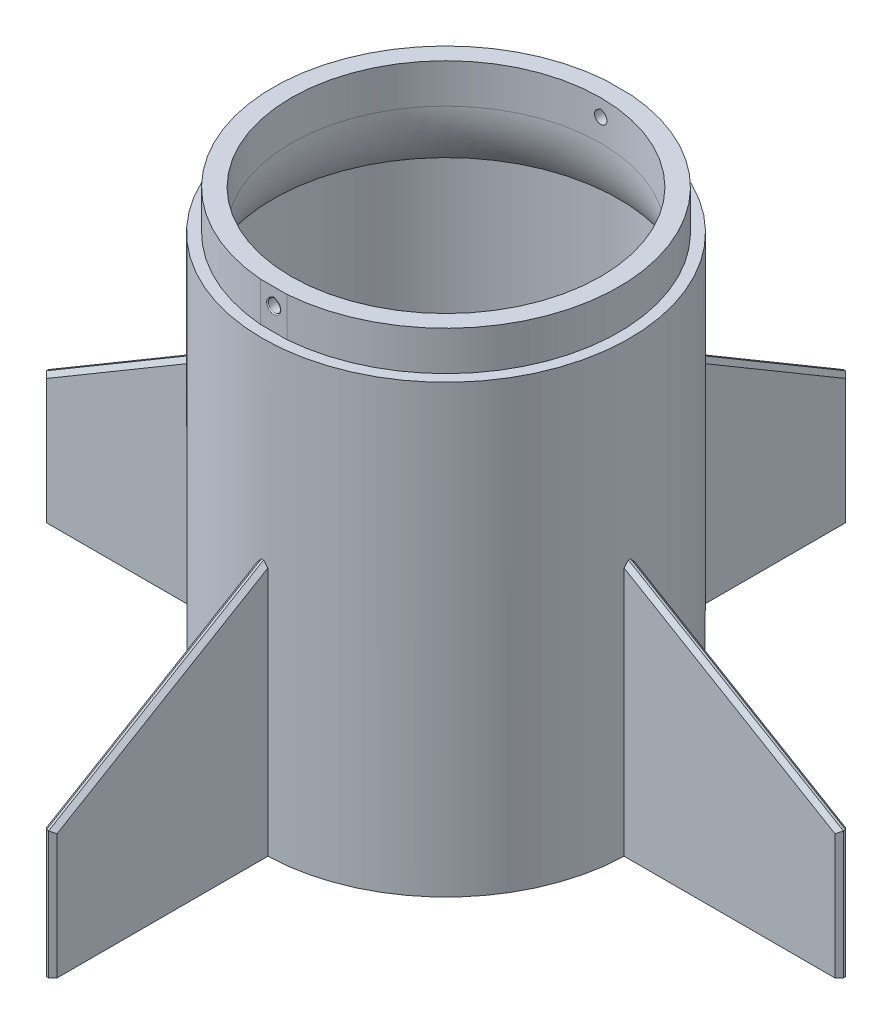
SolidWorks part; units mm, degrees
ref_plane "Front Plane" through (0, 0, 0) normal (0, 0, 1) x (1, 0, 0)
ref_plane "Top Plane" through (0, 0, 0) normal (0, 1, 0) x (1, 0, 0)
ref_plane "Right Plane" through (0, 0, 0) normal (1, 0, 0) x (0, 0, -1)
sketch "Sketch1" plane through (0, 0, 0) normal (0, 0, 1) x (1, 0, 0)
  line L0 (0, 21.7162) -> (0, -17.3677) construction
  line L2 (-43.9039, 83.2349) -> (-41.3639, 83.2349)
  line L3 (-43.9039, 83.2349) -> (-43.9039, -23.4451)
  line L4 (-43.9039, -23.4451) -> (-41.3639, -23.4451)
  line L5 (-41.3639, 83.2349) -> (-41.3639, -23.4451)
  line L6 (-41.3639, 83.2349) -> (-37.0459, 83.2349)
  line L7 (-41.3639, 83.2349) -> (-41.3639, 92.6329)
  line L8 (-41.3639, 92.6329) -> (-37.0459, 92.6329)
  line L9 (-37.0459, 83.2349) -> (-37.0459, 92.6329)
  arc A0 (-37.0459, 83.2349) -> (-41.3639, 69.5119) centre (-61.0112, 83.2349) cw
  point P12 (0, 0)
  dimension "D4" = 4.318
  dimension "D1" = 43.9039
  dimension "D2" = 2.54
  dimension "D3" = 106.68
  dimension "D5" = 9.398
revolve "Revolve1" add sketch "Sketch1" angle 360 about L0
sketch "Sketch4" plane through (0, 0, 0) normal (1, 0, 0) x (0, 0, -1)
  line L0 (43.8058, -23.4451) -> (43.8058, 37.5149)
  line L1 (43.8058, 37.5149) -> (95.3447, 7.0349)
  line L2 (95.3447, 7.0349) -> (95.3447, -23.4451)
  line L3 (95.3447, -23.4451) -> (43.8058, -23.4451)
  line L4 (44.4302, 37.5149) -> (96.2667, 37.5149) construction
  dimension "D1" = 60.96
  dimension "D2" = 30.48
  dimension "D3" = 30.6
extrude "Boss-Extrude3" add sketch "Sketch4" along normal mid plane 2.54
fillet "Chamfer1" radius 1.016 4 edges at (-1.27, -8.2051, -95.3447) (1.27, -8.2051, -95.3447) (-1.27, 22.2513, -69.6151) (1.27, 22.2513, -69.6151) profile chamfer
pattern_circular "CirPattern6" count 4 over 360 about axis through (0, 0, 0) along (0, 1, 0) of "Boss-Extrude3", "Chamfer1"
sketch "Sketch5" plane through (0, 83.2349, 0) normal (0, 1, 0) x (1, 0, 0)
  circle A0 centre (0, 0) radius 43.9039
  dimension "D1" = 87.8078
sketch "Sketch6" plane through (0, 0, 0) normal (0, 0, 1) x (1, 0, 0)
  line L0 (43.9039, 83.2349) -> (-43.9039, 83.2349) construction
  line L1 (43.9039, 83.2349) -> (-43.9039, 83.2349)
  line L2 (-0.771, 89.8529) -> (0, 90.3237)
  line L3 (0, 90.3237) -> (0.771, 89.8529)
  line L4 (0, 88.5901) -> (0, 83.2349)
  arc A0 (-0.771, 89.8529) -> (0.771, 89.8529) centre (0, 88.5901) ccw
extrude "Cut-Extrude6" cut sketch "Sketch6" against normal through all both and the other way through all
sketch "Sketch7" plane through (0, 92.6329, 0) normal (0, 1, 0) x (1, 0, 0)
  line L0 (-3.2004, 41.3639) -> (3.2004, 41.3639)
  line L1 (-3.2004, 41.2399) -> (3.2004, 41.2399)
  circle A1 centre (0, 0) radius 41.3639
  circle A2 centre (0, 0) radius 41.3639
  point P6 (0, 41.3639)
  circle M3 centre (0, 0) radius 41.3639
  dimension "D1" = 0
extrude "Cut-Extrude7" cut sketch "Sketch7" against normal up to surface (9.398 mm away) and the other way through all contours L1 M3
pattern_circular "CirPattern7" count 2 every 180 about axis through (0, 21.7162, 0) along (0, 1, 0) of "Cut-Extrude7"
fillet "Fillet1" radius 0.254 6 edges at (-0.3855, 90.0883, 41.2399) (0.3855, 90.0883, 41.2399) (0, 87.1106, 41.2399) (0.3855, 90.0883, -41.2399) (-0.3855, 90.0883, -41.2399) (0, 87.1106, -41.2399)
